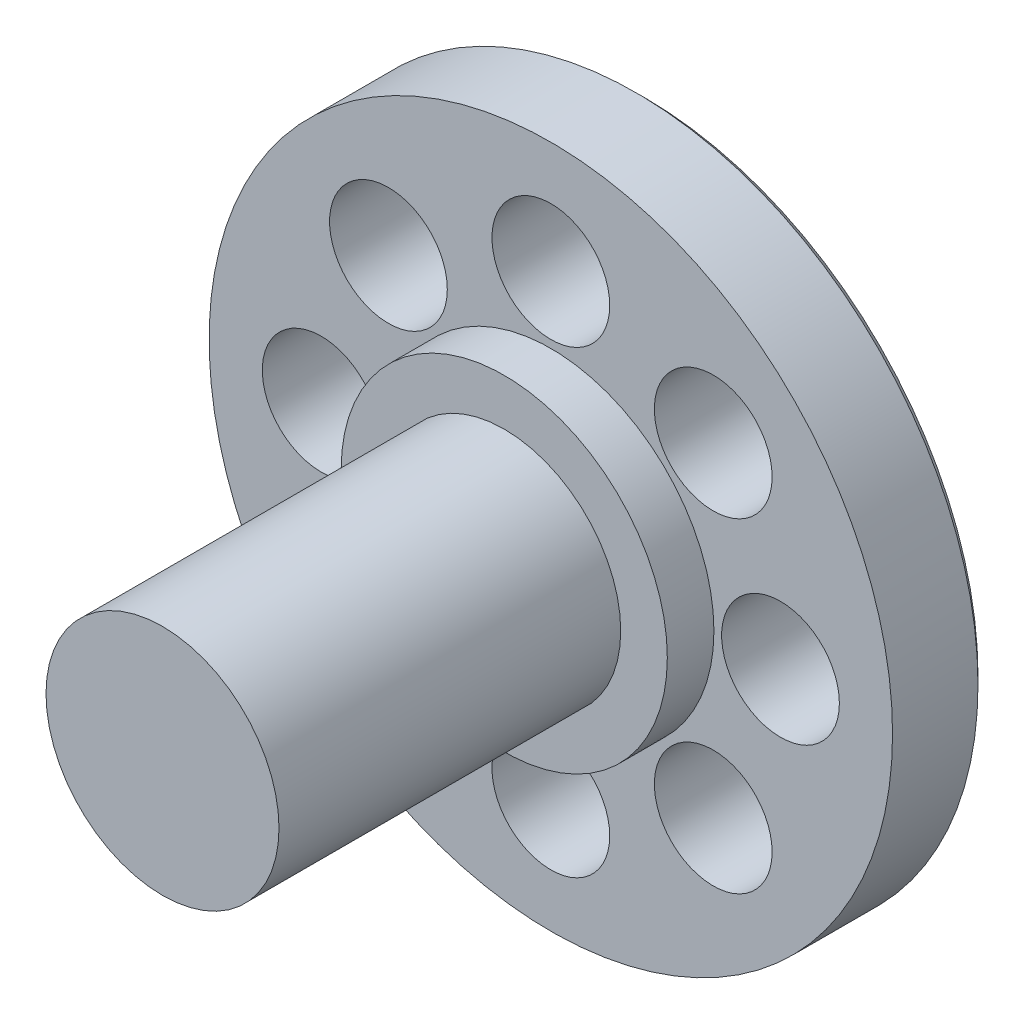
SolidWorks part; units mm, degrees
material "ABS PC"
ref_plane "Front Plane" through (0, 0, 0) normal (0, 0, 1) x (1, 0, 0)
ref_plane "Top Plane" through (0, 0, 0) normal (0, 1, 0) x (1, 0, 0)
ref_plane "Right Plane" through (0, 0, 0) normal (1, 0, 0) x (0, 0, -1)
sketch "Sketch1" plane through (0, 0, 0) normal (0, 0, 1) x (1, 0, 0)
  circle A0 centre (0, 0) radius 22
  circle A2 centre (0, 14.785) radius 3.79
  circle A3 centre (10.4546, 10.4546) radius 3.79
  circle A4 centre (14.785, 0) radius 3.79
  circle A5 centre (10.4546, -10.4546) radius 3.79
  circle A6 centre (0, -14.785) radius 3.79
  circle A7 centre (-10.4546, -10.4546) radius 3.79
  circle A8 centre (-14.785, 0) radius 3.79
  circle A9 centre (-10.4546, 10.4546) radius 3.79
  circle A10 centre (0, 0) radius 9
  point P22 (0, 0)
  dimension "D1" = 44
  dimension "D3" = 7.58
  dimension "D5" = 18
  dimension "D4" = 8
extrude "Boss-Extrude1" add sketch "Sketch1" along normal blind 6
sketch "Sketch2" plane through (0, 0, 6) normal (0, 0, 1) x (1, 0, 0)
  circle A0 centre (0, 0) radius 10.5
  dimension "D1" = 21
extrude "Boss-Extrude2" add sketch "Sketch2" along normal blind 25
sketch "Sketch3" plane through (0, 0, 0) normal (0, 0, -1) x (-1, 0, 0)
  circle A0 centre (0, 0) radius 9
  circle A1 centre (0, 0) radius 5.75
  dimension "D1" = 11.5
extrude "Boss-Extrude3" add sketch "Sketch3" against normal up to surface (6 mm away) up to face at (9, 0, 6)
chamfer "Chamfer1" distance 0.5 angle 45 10 edges at (-5.75, 0, 0) (-6.6646, 10.4546, 0) (-10.995, 0, 0) (-6.6646, -10.4546, 0) (3.79, -14.785, 0) (14.2446, -10.4546, 0) (18.575, 0, 0) (14.2446, 10.4546, 0) (3.79, 14.785, 0) (22, 0, 0)
sketch "Sketch4" plane through (0, 0, 31) normal (0, 0, 1) x (1, 0, 0)
  circle A0 centre (0, 0) radius 7.5
  circle A1 centre (0, 0) radius 10.5
  dimension "D1" = 15
extrude "Cut-Extrude2" cut sketch "Sketch4" against normal blind 22
sketch "Sketch5" plane through (0, 0, 0) normal (0, 0, -1) x (-1, 0, 0)
  circle A1 centre (0, 0) radius 5.75
  dimension "D1" = 11.5
extrude "Cut-Extrude3" cut sketch "Sketch5" against normal blind 8
